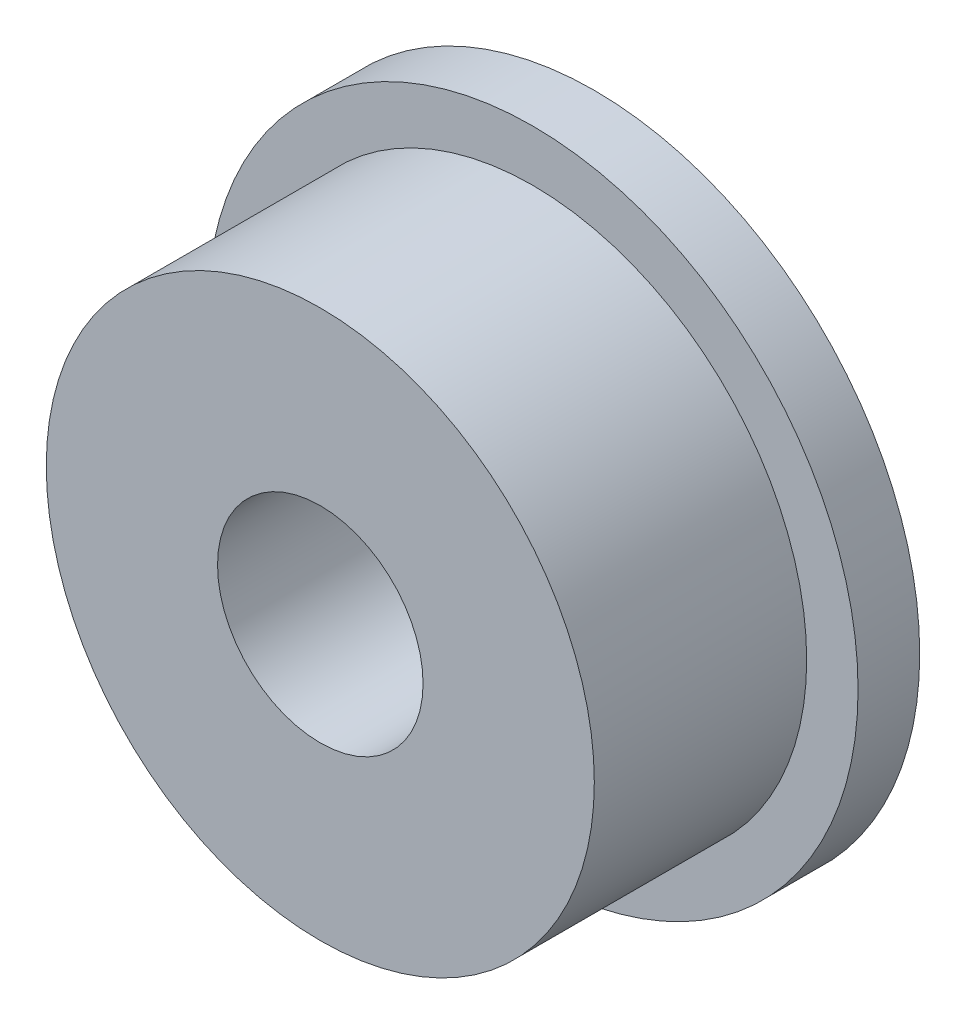
SolidWorks part; units mm, degrees
material "AISI 4340 Steel, normalized"
ref_plane "Front Plane" through (0, 0, 0) normal (0, 0, 1) x (1, 0, 0)
ref_plane "Top Plane" through (0, 0, 0) normal (0, 1, 0) x (1, 0, 0)
ref_plane "Right Plane" through (0, 0, 0) normal (1, 0, 0) x (0, 0, -1)
sketch "Sketch1" plane through (0, 0, 0) normal (0, 0, 1) x (1, 0, 0)
  circle A0 centre (0, 0) radius 4
  circle A1 centre (0, 0) radius 1.5
extrude "F693ZZ_External_Envelope_3x8x4" add sketch "Sketch1" along normal blind 4 from offset 3
sketch "Sketch2" plane through (0, 0, 0) normal (0, 0, 1) x (1, 0, 0)
  circle A0 centre (0, 0) radius 4.75
  circle A1 centre (0, 0) radius 1.5
extrude "Flange_9p5x0p9" add sketch "Sketch2" along normal blind 0.9 from offset 3
